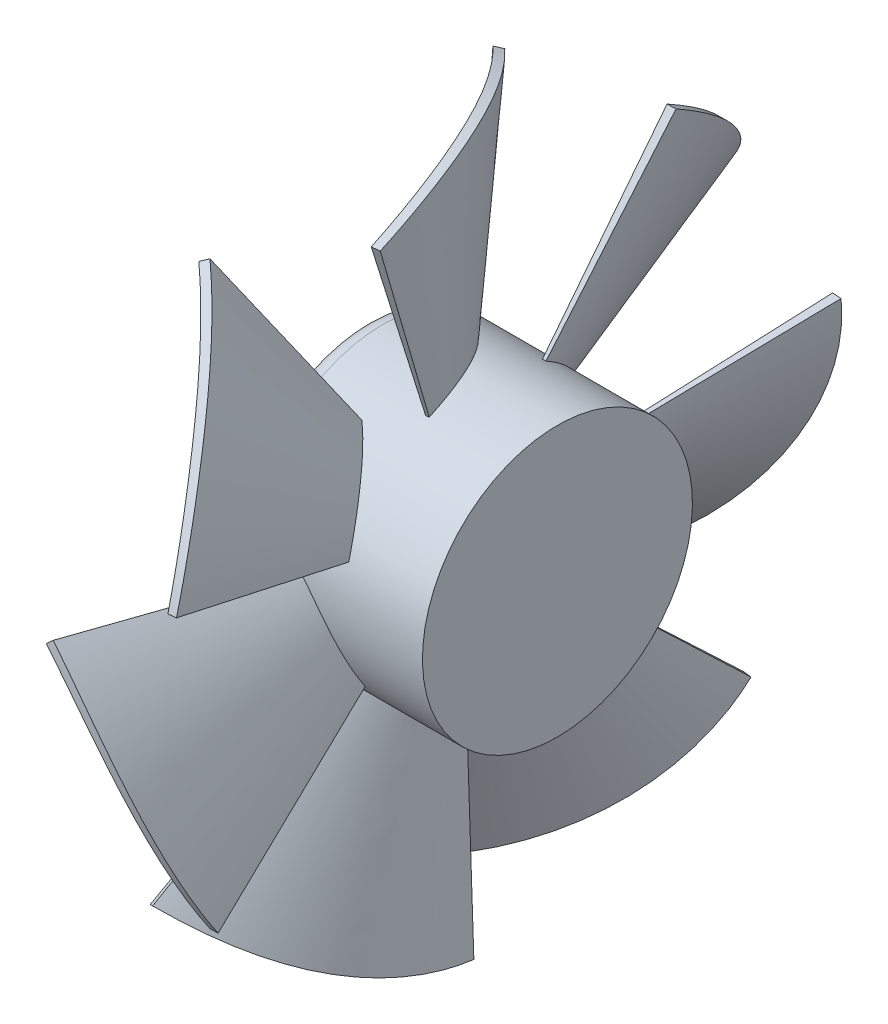
SolidWorks part; units mm, degrees
material "PW100:Mi:0:30:C1:0:1:2:Re:16:"
ref_plane "Front" through (0, 0, 0) normal (0, 0, 1) x (1, 0, 0)
ref_plane "Top" through (0, 0, 0) normal (0, 1, 0) x (1, 0, 0)
ref_plane "Right" through (0, 0, 0) normal (1, 0, 0) x (0, 0, -1)
sketch "Support-Front" plane through (0, 0, 0) normal (0, 0, 1) x (1, 0, 0)
  line L0 (-25.4, 0) -> (-4, 0) construction
  line L1 (-25.4, -15) -> (-25.4, 15)
  line L2 (-25.4, 15) -> (-4, 15)
  line L3 (-25.4, -15) -> (-4, -15)
  line L4 (-4, 15) -> (-4, -15)
  line L5 (-14.7, 15) -> (-14.7, -15) construction
  line L6 (-4, 15) -> (0, 15) construction
  line L7 (-4, -15) -> (0, -15) construction
  line L8 (0, 15) -> (0, -15) construction
  line L11 (-14.7, 15) -> (-14.7, 38) construction
  line L12 (-14.7, -15) -> (-14.7, -38) construction
  point P12 (0, 0)
  point P14 (-14.7, 0)
  dimension "Width" = 25.4
  dimension "Diam-Body" = 30
  dimension "Diam-Fan" = 76
  dimension "Dist-Fan" = 4
sketch "Support-Right" plane through (0, 0, 0) normal (1, 0, 0) x (0, 0, -1)
  circle A0 centre (0, 0) radius 38
sketch "Support-Fan-Blade-Top" plane through (0, 0, 0) normal (0, 1, 0) x (-1, 0, 0)
  line L0 (14.7, 0) -> (10.7835, 14.6165) construction
  line L1 (23.3794, -12.3955) -> (10.7835, 14.6165) construction
  line L2 (17.0815, 1.1105) -> (14.7, 0) construction
  line L4 (25.4, 0) -> (10.7835, 14.6165) construction
  line L5 (25.4, 0) -> (4, 0) construction
  line L6 (9.7873, 14.5293) -> (10.7835, 14.6165)
  line L7 (22.6723, -13.1026) -> (23.3794, -12.3955)
  arc A0 (10.7835, 14.6165) -> (23.3794, -12.3955) centre (54.1888, 18.4139) ccw
  arc A1 (9.7873, 14.5293) -> (22.6723, -13.1026) centre (54.1888, 18.4139) ccw
  dimension "Angle-Fan-Blade" = 65
  dimension "D1" = 10
  dimension "D3" = 45
  dimension "D2" = 1
ref_plane "Plane-Angle-Fan-Blade" through (-12.0745, 0, 5.6304) normal (-0.9063, 0, 0.4226) x (0.4226, 0, 0.9063)
ref_plane "Plane-Top-Fan-Blade" through (0, 38, 0) normal (0, 1, 0) x (-1, 0, 0)
sketch "Sketch-Blade-Bottom" plane through (0, 0, 0) normal (0, 1, 0) x (1, 0, 0)
  point P0 (-14.7, 0)
sketch "Sketch-Blade-Top" plane through (0, 38, 0) normal (0, 1, 0) x (-1, 0, 0)
  line L2 (10.7835, 14.6165) -> (9.7873, 14.5293)
  line L3 (22.6723, -13.1026) -> (23.3794, -12.3955)
  line L4 (10.7835, 14.6165) -> (9.7873, 14.5293)
  line L5 (22.6723, -13.1026) -> (23.3794, -12.3955)
  arc A3 (9.7873, 14.5293) -> (22.6723, -13.1026) centre (54.1888, 18.4139) ccw
  arc A4 (10.7835, 14.6165) -> (23.3794, -12.3955) centre (54.1888, 18.4139) ccw
  arc A5 (9.7873, 14.5293) -> (22.6723, -13.1026) centre (54.1888, 18.4139) ccw
  arc A6 (10.7835, 14.6165) -> (23.3794, -12.3955) centre (54.1888, 18.4139) ccw
  dimension "D1" = 0
ref_plane "Plane-Right-Cut" through (-25.4, 0, 0) normal (1, 0, 0) x (0, 0, -1)
sketch "Sketch5" plane through (0, 0, 0) normal (0, 0, 1) x (1, 0, 0)
  line L0 (-4, 15) -> (-4, -15) construction
  line L1 (-25.4, -15) -> (-25.4, 15) construction
  line L4 (-4, 15) -> (-4, 0)
  line L5 (-25.4, 0) -> (-25.4, 15)
  line L6 (-25.4, 0) -> (-4, 0)
  line L7 (-25.4, 15) -> (-4, 15) construction
  line L8 (-25.4, 0) -> (-4, 0) construction
  line L9 (-25.4, 0) -> (-4, 0) construction
  line L10 (-25.4, 15) -> (-4, 15)
revolve "Body" add sketch "Sketch5" angle 360 about L9
loft "Loft-Fan-Blade" add profiles "Sketch-Blade-Top", "Sketch-Blade-Bottom"
pattern_circular "CirPattern1" count 7 over 360 about axis through (-25.4, 0, 0) along (1, 0, 0) of "Loft-Fan-Blade"
sketch "Sketch-Cut-Blade" plane through (0, 0, 0) normal (1, 0, 0) x (0, 0, -1)
  circle A0 centre (0, 0) radius 38 construction
  circle A1 centre (0, 0) radius 38
extrude "Cut-Fan-Blade" cut sketch "Sketch-Cut-Blade" against normal through all flip side to cut
fillet "Cosmetic-Fillet" radius 2 1 edges at (-25.4, -15, 0)
equation "\"Angle-Blade@Plane-Angle-Fan-Blade\" = \"Angle-Fan-Blade@Support-Fan-Blade-Top\""
equation "\"Rad@Cosmetic-Fillet\" = \"Dist-Fan@Support-Front\" / 2"
